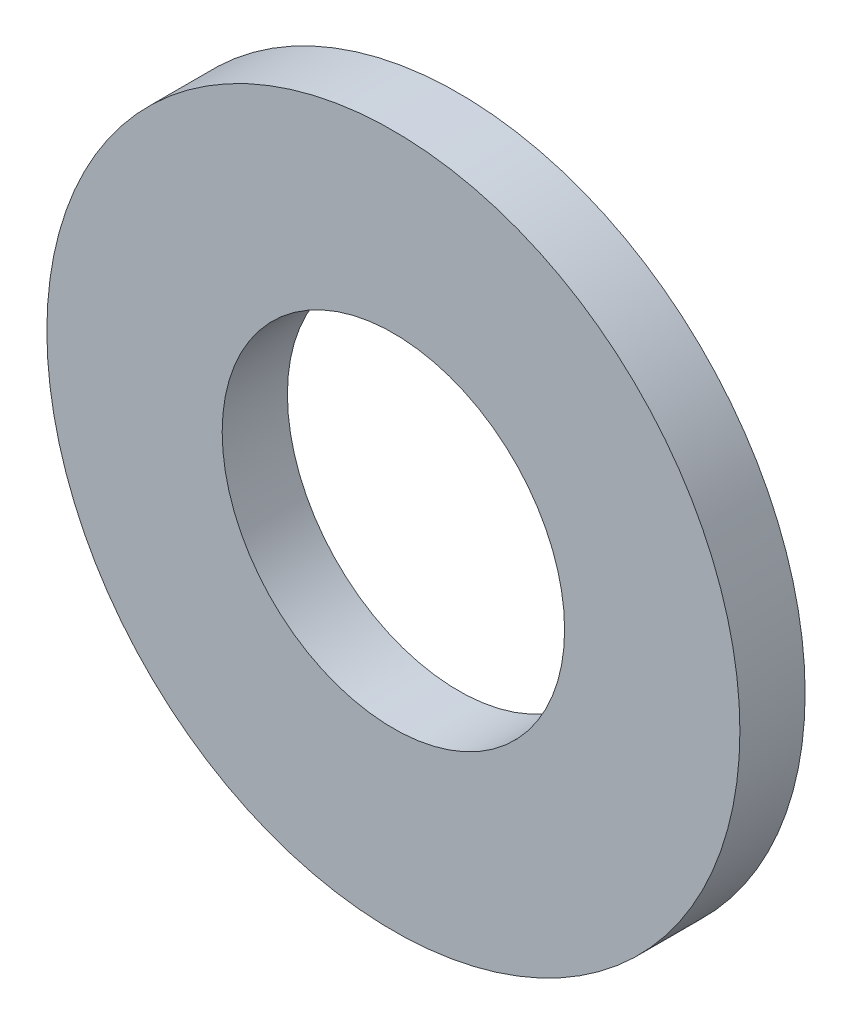
SolidWorks part; units mm, degrees
ref_plane "Спереди" through (0, 0, 0) normal (0, 0, 1) x (1, 0, 0)
ref_plane "Сверху" through (0, 0, 0) normal (0, 1, 0) x (1, 0, 0)
ref_plane "Справа" through (0, 0, 0) normal (1, 0, 0) x (0, 0, -1)
sketch "Эскиз1" plane through (0, 0, 0) normal (0, 0, 1) x (1, 0, 0)
  circle A0 centre (0, 0) radius 8.5
  circle A1 centre (0, 0) radius 4.2
  dimension "D1" = 17
  dimension "D2" = 8.4
extrude "Вытянуть1" add sketch "Эскиз1" along normal blind 1.6
